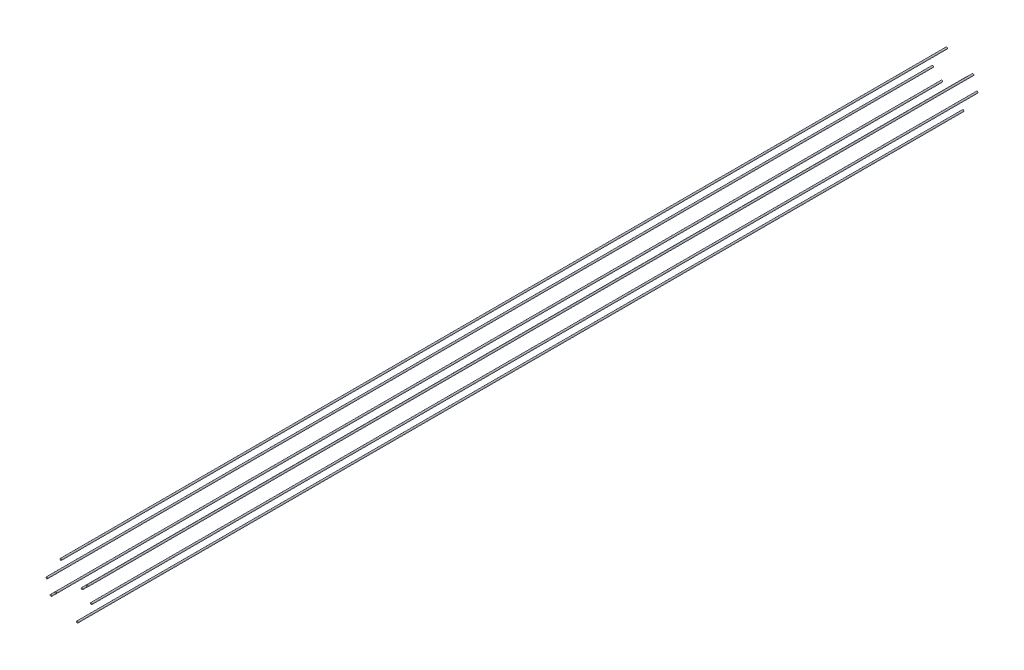
SolidWorks part; units mm, degrees
ref_plane "Front Plane" through (0, 0, 0) normal (0, 0, 1) x (1, 0, 0)
ref_plane "Top Plane" through (0, 0, 0) normal (0, 1, 0) x (1, 0, 0)
ref_plane "Right Plane" through (0, 0, 0) normal (1, 0, 0) x (0, 0, -1)
sketch3d "3DSketch1"
  line L0 (-14.9994, -44.8632, 531.0423) -> (-15.2373, -44.8632, 250.2904) construction
  line L1 (-6.4592, -30.8632, 234.0423) -> (-6.4592, -30.8632, 531.0423) construction
  line L2 (-14.9994, -44.8632, 531.0423) -> (-15.2373, -44.8632, 250.2904)
  line L3 (-6.4592, -30.8632, 234.0423) -> (-6.4592, -30.8632, 531.0423)
  line L4 (3.5408, -58.8632, 234.0423) -> (3.5408, -58.8632, 531.0423) construction
  line L5 (12.5408, -44.8632, 531.0423) -> (12.5408, -44.8632, 250.2904) construction
  line L6 (-12.4592, -52.8632, 234.0423) -> (-12.4592, -52.8632, 531.0423) construction
  line L7 (-9.4592, -49.8632, 234.0423) -> (-9.4592, -49.8632, 531.0423) construction
  line L8 (6.4138, -39.8632, 234.0423) -> (6.4138, -39.8632, 531.0423) construction
  line L9 (9.5408, -36.8632, 234.0423) -> (9.5408, -36.8632, 531.0423) construction
  line L10 (3.5408, -58.8632, 234.0423) -> (3.5408, -58.8632, 531.0423)
  line L11 (12.5408, -44.8632, 531.0423) -> (12.5408, -44.8632, 250.2904)
  line L12 (-12.4592, -52.8632, 234.0423) -> (-12.4592, -52.8632, 531.0423)
  line L13 (-9.4592, -49.8632, 234.0423) -> (-9.4592, -49.8632, 531.0423)
  line L14 (6.4138, -39.8632, 234.0423) -> (6.4138, -39.8632, 531.0423)
  line L15 (9.5408, -36.8632, 234.0423) -> (9.5408, -36.8632, 531.0423)
sketch "Sketch2" plane through (0, 0, 297) normal (0, 0, 1) x (1, 0, 0)
  circle A0 centre (9.5408, -36.8632) radius 0.5 construction
  circle A1 centre (6.4138, -39.8632) radius 0.5 construction
  circle A2 centre (12.081, -44.8632) radius 0.5 construction
  circle A3 centre (3.5408, -58.8632) radius 0.5 construction
  circle A4 centre (-9.4592, -49.8632) radius 0.5 construction
  circle A5 centre (-12.4592, -52.8632) radius 0.5 construction
  circle A6 centre (-14.9994, -44.8632) radius 0.5 construction
  circle A7 centre (-6.4592, -30.8632) radius 0.5 construction
  circle A8 centre (9.5408, -36.8632) radius 0.5
  circle A9 centre (6.4138, -39.8632) radius 0.5
  circle A10 centre (12.081, -44.8632) radius 0.5
  circle A11 centre (3.5408, -58.8632) radius 0.5
  circle A12 centre (-9.4592, -49.8632) radius 0.5
  circle A13 centre (-12.4592, -52.8632) radius 0.5
  circle A14 centre (-14.9994, -44.8632) radius 0.5
  circle A15 centre (-6.4592, -30.8632) radius 0.5
sweep "Sweep1" add profiles "Sketch2" path "3DSketch1"
sketch "Sketch3" plane through (0, 0, 297) normal (0, 0, -1) x (-1, 0, 0)
  circle A0 centre (-9.5408, -36.8632) radius 0.5 construction
  circle A1 centre (-6.4138, -39.8632) radius 0.5 construction
  circle A2 centre (-12.081, -44.8632) radius 0.5 construction
  circle A3 centre (-3.5408, -58.8632) radius 0.5 construction
  circle A4 centre (12.4592, -52.8632) radius 0.5 construction
  circle A5 centre (9.4592, -49.8632) radius 0.5 construction
  circle A6 centre (14.9994, -44.8632) radius 0.5 construction
  circle A7 centre (6.4592, -30.8632) radius 0.5 construction
  circle A8 centre (-9.5408, -36.8632) radius 0.5
  circle A9 centre (-6.4138, -39.8632) radius 0.5
  circle A10 centre (-12.081, -44.8632) radius 0.5
  circle A11 centre (-3.5408, -58.8632) radius 0.5
  circle A12 centre (12.4592, -52.8632) radius 0.5
  circle A13 centre (9.4592, -49.8632) radius 0.5
  circle A14 centre (14.9994, -44.8632) radius 0.5
  circle A15 centre (6.4592, -30.8632) radius 0.5
extrude "Boss-Extrude1" add sketch "Sketch3" along normal blind 304.8
